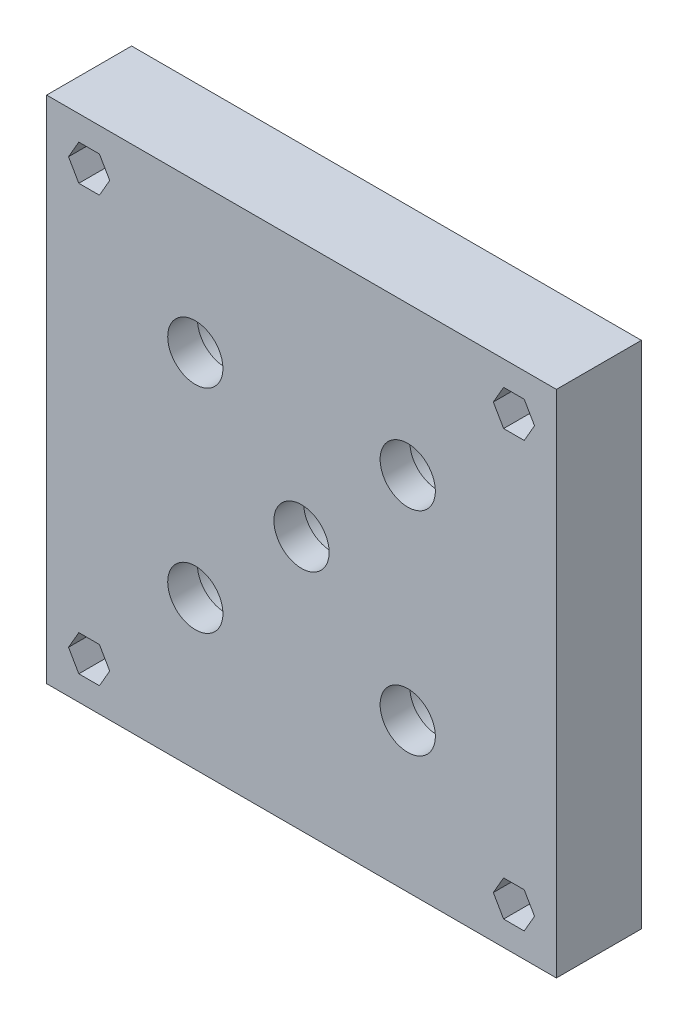
SolidWorks part; units mm, degrees
ref_plane "Front Plane" through (0, 0, 0) normal (0, 0, 1) x (1, 0, 0)
ref_plane "Top Plane" through (0, 0, 0) normal (0, 1, 0) x (1, 0, 0)
ref_plane "Right Plane" through (0, 0, 0) normal (1, 0, 0) x (0, 0, -1)
sketch "Sketch1" plane through (0, 0, 0) normal (0, 0, 1) x (1, 0, 0)
  line L1 (-30, 30) -> (30, 30)
  line L2 (-30, 30) -> (-30, -30)
  line L3 (-30, -30) -> (30, -30)
  line L4 (30, 30) -> (30, -30)
  line L5 (-30, 30) -> (30, -30) construction
  line L6 (-30, -30) -> (30, 30) construction
  point P0 (0, 0)
  dimension "D1" = 60
  dimension "D2" = 60
extrude "Boss-Extrude1" add sketch "Sketch1" along normal blind 10
sketch "Sketch2" plane through (0, 0, 10) normal (0, 0, 1) x (1, 0, 0)
  line L0 (-25, 20) -> (-25, 30)
  line L1 (-30, 30) -> (-20, 30)
  line L2 (-30, 30) -> (-30, 20)
  line L3 (-30, 20) -> (-20, 20)
  line L4 (-20, 30) -> (-20, 20)
  circle A0 centre (-25, 25) radius 1.15
  circle A1 centre (25, 25) radius 1.15
  circle A2 centre (25, -25) radius 1.15
  circle A3 centre (-25, -25) radius 1.15
  point P9 (0, 0)
  point P20 (0, 0)
  dimension "D3" = 2.3
  dimension "D1" = 10
  dimension "D2" = 10
  dimension "D4" = 4
extrude "Cut-Extrude1" cut sketch "Sketch2" against normal through all contours L0 A0 | L0 A0 | A1 | A2 | A3
sketch "Sketch3" plane through (0, 0, 10) normal (0, 0, 1) x (1, 0, 0)
  line L0 (0, 0) -> (24.9087, 0)
  line L1 (-22.5751, 25) -> (-23.7876, 27.1)
  line L2 (-23.7876, 27.1) -> (-26.2124, 27.1)
  line L3 (-26.2124, 27.1) -> (-27.4249, 25)
  line L4 (-27.4249, 25) -> (-26.2124, 22.9)
  line L5 (-26.2124, 22.9) -> (-23.7876, 22.9)
  line L6 (-23.7876, 22.9) -> (-22.5751, 25)
  line L7 (0, 0) -> (0, 14.5359)
  line L8 (23.7876, 22.9) -> (22.5751, 25)
  line L9 (26.2124, 22.9) -> (23.7876, 22.9)
  line L10 (27.4249, 25) -> (26.2124, 22.9)
  line L11 (26.2124, 27.1) -> (27.4249, 25)
  line L12 (23.7876, 27.1) -> (26.2124, 27.1)
  line L13 (22.5751, 25) -> (23.7876, 27.1)
  line L14 (26.2124, -22.9) -> (23.7876, -22.9)
  line L15 (27.4249, -25) -> (26.2124, -22.9)
  line L16 (26.2124, -27.1) -> (27.4249, -25)
  line L17 (23.7876, -27.1) -> (26.2124, -27.1)
  line L18 (22.5751, -25) -> (23.7876, -27.1)
  line L19 (23.7876, -22.9) -> (22.5751, -25)
  line L20 (-23.7876, -22.9) -> (-22.5751, -25)
  line L21 (-26.2124, -22.9) -> (-23.7876, -22.9)
  line L22 (-27.4249, -25) -> (-26.2124, -22.9)
  line L23 (-26.2124, -27.1) -> (-27.4249, -25)
  line L24 (-23.7876, -27.1) -> (-26.2124, -27.1)
  line L25 (-22.5751, -25) -> (-23.7876, -27.1)
  circle A0 centre (-25, 25) radius 2.1 construction
  circle M15 centre (-25, -25) radius 1.15
  circle M16 centre (25, -25) radius 1.15
  circle M17 centre (25, 25) radius 1.15
  circle M18 centre (-25, 25) radius 1.15
extrude "Cut-Extrude2" cut sketch "Sketch3" against normal blind 8 contours L5 L6 L1 L2 L3 L4 M18 | L13 L8 L9 L10 L11 L12 M17 | L14 L19 L18 L17 L16 L15 M16 | L25 L20 L21 L22 L23 L24 M15
sketch "Sketch5" plane through (0, 0, 0) normal (0, 0, -1) x (-1, 0, 0)
  circle A5 centre (-12.5, 12.5) radius 5.25
  circle A7 centre (12.5, 12.5) radius 5.25
  circle A10 centre (0, 0) radius 5.25
  circle A13 centre (-12.5, -12.5) radius 5.25
  circle A15 centre (12.5, -12.5) radius 5.25
extrude "Cut-Extrude4" cut sketch "Sketch5" against normal blind 6.5
sketch "Sketch6" plane through (0, 0, 6.5) normal (0, 0, -1) x (-1, 0, 0)
  circle A0 centre (-12.5, 12.5) radius 3.25
  circle A1 centre (12.5, 12.5) radius 3.25
  circle A2 centre (0, 0) radius 3.25
  circle A3 centre (-12.5, -12.5) radius 3.25
  circle A4 centre (12.5, -12.5) radius 3.25
extrude "Cut-Extrude5" cut sketch "Sketch6" against normal through all
